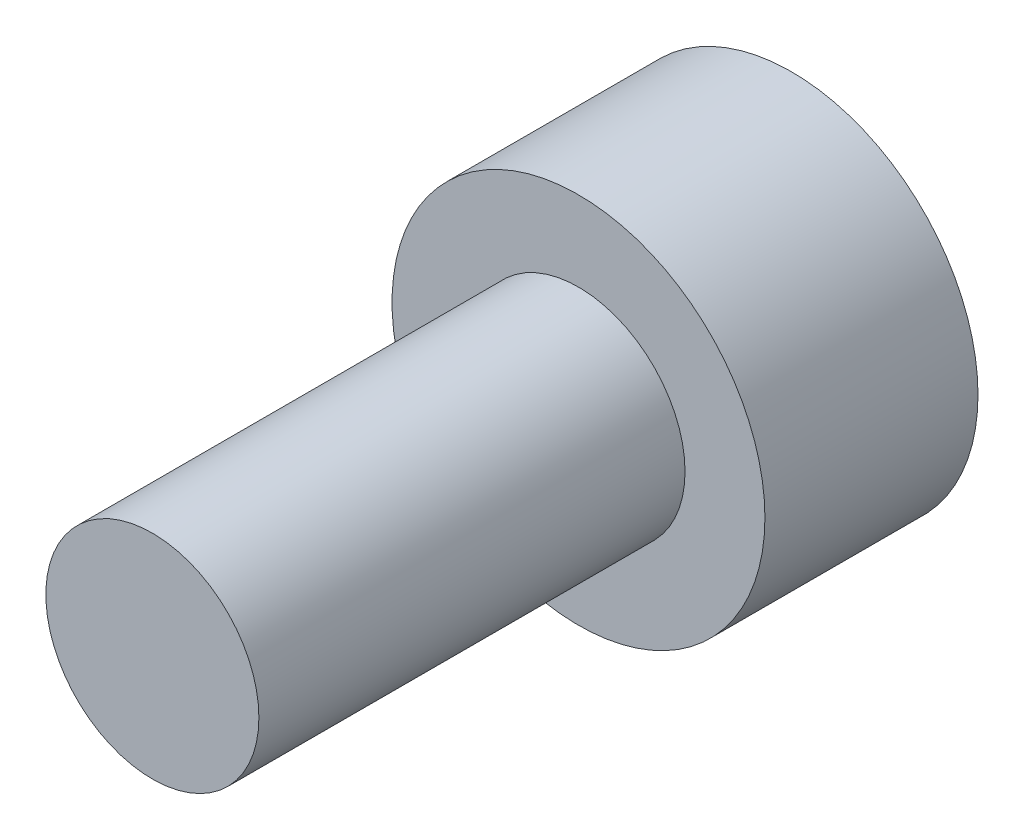
SolidWorks part; units mm, degrees
ref_plane "Front Plane" through (0, 0, 0) normal (0, 0, 1) x (1, 0, 0)
ref_plane "Top Plane" through (0, 0, 0) normal (0, 1, 0) x (1, 0, 0)
ref_plane "Right Plane" through (0, 0, 0) normal (1, 0, 0) x (0, 0, -1)
sketch "Sketch1" plane through (0, 0, 0) normal (0, 0, 1) x (1, 0, 0)
  circle A0 centre (0, 0) radius 2
  dimension "D1" = 4
extrude "Boss-Extrude1" add sketch "Sketch1" along normal blind 8
sketch "Sketch2" plane through (0, 0, 0) normal (0, 0, 1) x (1, 0, 0)
  circle A0 centre (0, 0) radius 3.5
  dimension "D1" = 7
extrude "Boss-Extrude2" add sketch "Sketch2" against normal blind 4
